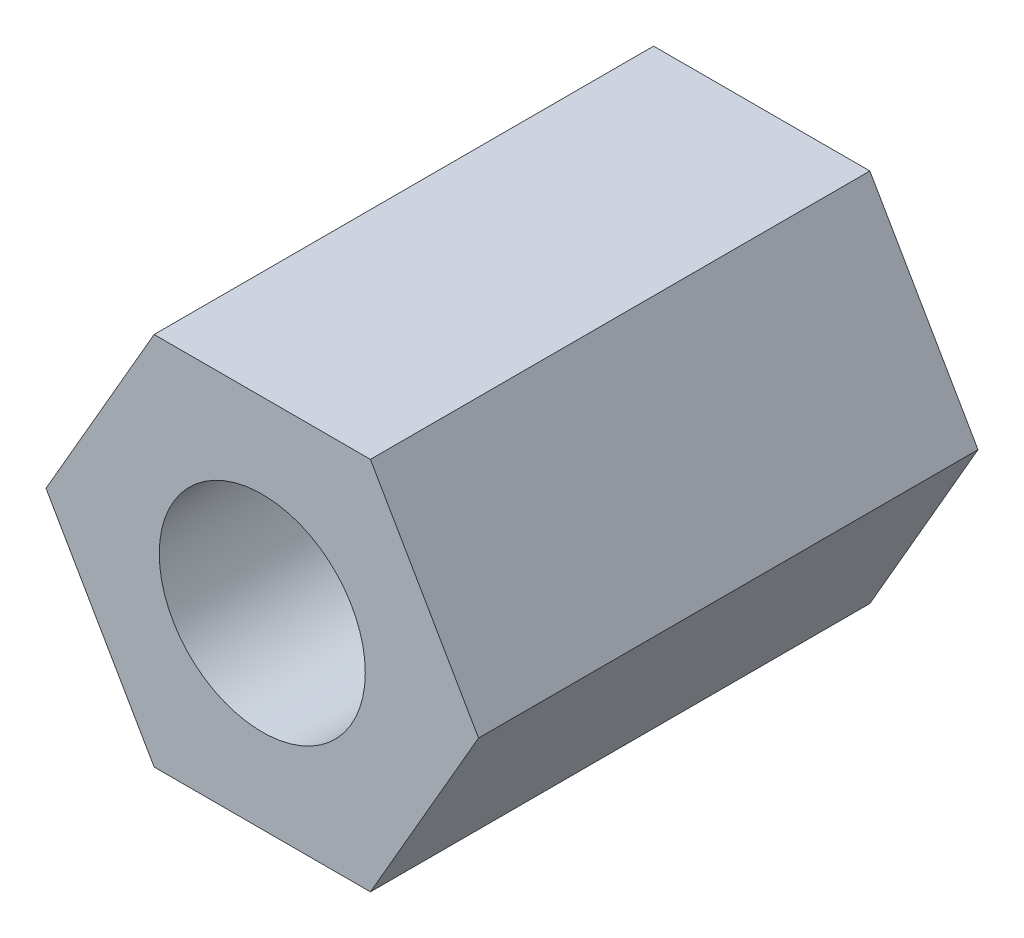
SolidWorks part; units mm, degrees
ref_plane "前视基准面" through (0, 0, 0) normal (0, 0, 1) x (1, 0, 0)
ref_plane "上视基准面" through (0, 0, 0) normal (0, 1, 0) x (1, 0, 0)
ref_plane "右视基准面" through (0, 0, 0) normal (1, 0, 0) x (0, 0, -1)
sketch "草图1" plane through (0, 0, 0) normal (0, 0, 1) x (1, 0, 0)
  line L0 (0, 0) -> (4.3863, 0) construction
  line L1 (0, 0) -> (0, 4.0694) construction
  line L3 (3.4641, 0) -> (1.7321, 3)
  line L4 (1.7321, 3) -> (-1.7321, 3)
  line L5 (-1.7321, 3) -> (-3.4641, 0)
  line L6 (-3.4641, 0) -> (-1.7321, -3)
  line L7 (-1.7321, -3) -> (1.7321, -3)
  line L8 (1.7321, -3) -> (3.4641, 0)
  circle A0 centre (0, 0) radius 3 construction
  dimension "D1" = 6
extrude "凸台-拉伸1" add sketch "草图1" along normal blind 8
sketch "草图4" plane through (0, 0, 0) normal (0, 0, -1) x (-1, 0, 0)
  point P0 (0, 0)
hole_wizard "M4 螺纹孔1" positions "草图4" profile "草图5" tap size "M4" standard "GB" end condition through all
sketch "草图5" plane through (0, 0, 0) normal (1, 0, 0) x (0, 1, 0)
  line L0 (0, 0) -> (0, 8)
  line L1 (0, 8) -> (1.65, 8)
  line L2 (1.65, 8) -> (1.65, 0.375)
  line L3 (1.65, 0.375) -> (2.025, 0)
  line L5 (2.025, 0) -> (0, 0)
  line L6 (-1.65, 0.375) -> (-2.025, 0) construction
  line L11 (0, -6.35) -> (0, 107.95) construction
  dimension "通孔螺纹孔钻头直径" = 3.3
  dimension "通孔螺纹孔钻头深度" = 8
  dimension "近端锥形沉头孔直径" = 4.05
  dimension "近端锥形沉头孔角度" = 90
